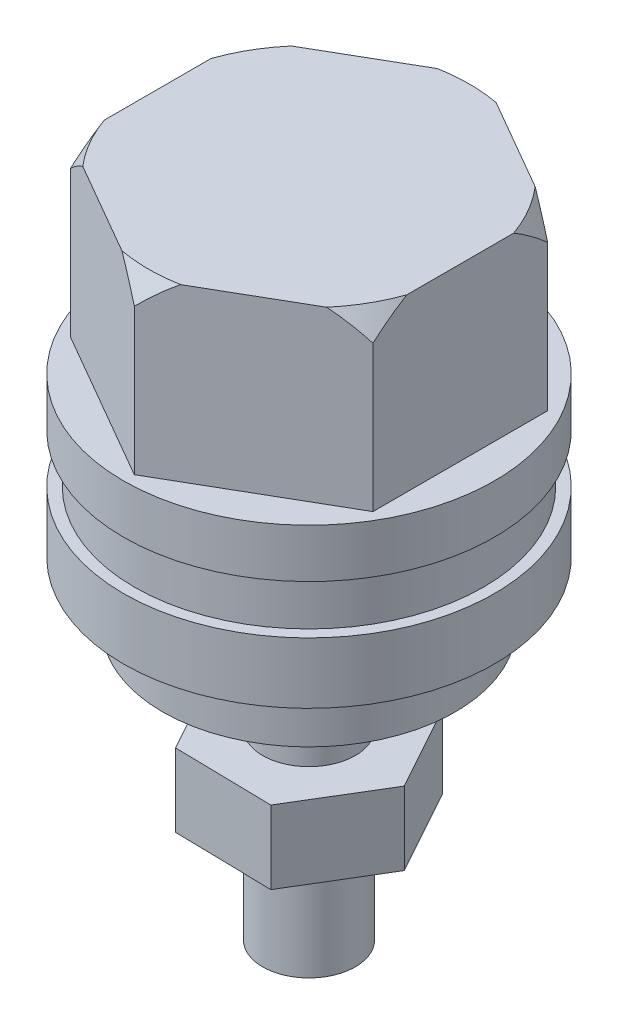
SolidWorks part; units mm, degrees
ref_plane "前视基准面" through (0, 0, 0) normal (0, 0, 1) x (1, 0, 0)
ref_plane "上视基准面" through (0, 0, 0) normal (0, 1, 0) x (1, 0, 0)
ref_plane "右视基准面" through (0, 0, 0) normal (1, 0, 0) x (0, 0, -1)
sketch "草图1" plane through (0, 0, 0) normal (0, 1, 0) x (1, 0, 0)
  circle A0 centre (0, 0) radius 6
  dimension "D1" = 12
extrude "凸台-拉伸1" add sketch "草图1" along normal blind 2.5
sketch "草图2" plane through (0, 2.5, 0) normal (0, 1, 0) x (1, 0, 0)
  circle A0 centre (0, 0) radius 7.6
  dimension "D1" = 15.2
extrude "凸台-拉伸2" add sketch "草图2" along normal blind 2.5
sketch "草图3" plane through (0, 5, 0) normal (0, 1, 0) x (1, 0, 0)
  circle A0 centre (0, 0) radius 7.15
  dimension "D1" = 14.3
extrude "凸台-拉伸3" add sketch "草图3" along normal blind 2 separate body
sketch "草图4" plane through (0, 7, 0) normal (0, 1, 0) x (1, 0, 0)
  circle A0 centre (0, 0) radius 7.6
extrude "凸台-拉伸4" add sketch "草图4" along normal blind 2 separate body
sketch "草图5" plane through (0, 9, 0) normal (0, 1, 0) x (1, 0, 0)
  line L1 (0, 7.1591) -> (-6.2, 3.5796)
  line L2 (-6.2, 3.5796) -> (-6.2, -3.5796)
  line L3 (-6.2, -3.5796) -> (0, -7.1591)
  line L4 (0, -7.1591) -> (6.2, -3.5796)
  line L5 (6.2, -3.5796) -> (6.2, 3.5796)
  line L6 (6.2, 3.5796) -> (0, 7.1591)
  circle A0 centre (0, 0) radius 6.2 construction
  dimension "D1" = 12.4
extrude "凸台-拉伸5" add sketch "草图5" along normal blind 7 separate body
ref_plane "基准面1" through (0, 0, 0) normal (-0.5, 0, 0.866) x (0.866, 0, 0.5)
sketch "草图7" plane through (0, 0, 0) normal (-0.5, 0, 0.866) x (0.866, 0, 0.5)
  line L0 (-6.2098, 16.6398) -> (-7.4416, 14.4831)
  line L1 (-7.4416, 14.4831) -> (-8.216, 16.6398)
  line L2 (-8.216, 16.6398) -> (-6.2098, 16.6398)
  line L3 (0, 16) -> (0, 9.5975) construction
  line L4 (-3.5796, 16) -> (3.5796, 16) construction
  point P8 (-6.4207, 16.6398)
  point P9 (-7.4937, 14.8449)
  point P10 (-6.2098, 16.6398)
  point P11 (-7.4416, 14.4831)
revolve "切除-旋转2" cut sketch "草图7" angle 360 about L3
sketch "草图8" plane through (0, 0, 0) normal (0, -1, 0) x (1, 0, 0)
  line L2 (1.95, 1.7944) -> (1.95, -1.7944)
  line L4 (-1.95, 1.7944) -> (-1.95, -1.7944)
  arc A0 (1.95, 1.7944) -> (-1.95, 1.7944) centre (0, 0) ccw
  arc A1 (-1.95, -1.7944) -> (1.95, -1.7944) centre (0, 0) ccw
  dimension "D1" = 5.3
  dimension "D2" = 3.9
extrude "凸台-拉伸6" add sketch "草图8" along normal blind 1.6
sketch "草图9" plane through (0, -1.6, 0) normal (0, -1, 0) x (1, 0, 0)
  circle A0 centre (0, 0) radius 1.9
  dimension "D1" = 3.8
extrude "凸台-拉伸7" add sketch "草图9" along normal blind 9.5
sketch "草图10" plane through (0, -1.6, 0) normal (0, -1, 0) x (1, 0, 0)
  line L1 (1.924, 3.4883) -> (-2.059, 3.4104)
  line L2 (-2.059, 3.4104) -> (-3.983, -0.078)
  line L3 (-3.983, -0.078) -> (-1.924, -3.4883)
  line L4 (-1.924, -3.4883) -> (2.059, -3.4104)
  line L5 (2.059, -3.4104) -> (3.983, 0.078)
  line L6 (3.983, 0.078) -> (1.924, 3.4883)
  circle A0 centre (0, 0) radius 3.45 construction
  dimension "D1" = 6.9
extrude "凸台-拉伸8" add sketch "草图10" along normal blind 3 from offset 2
